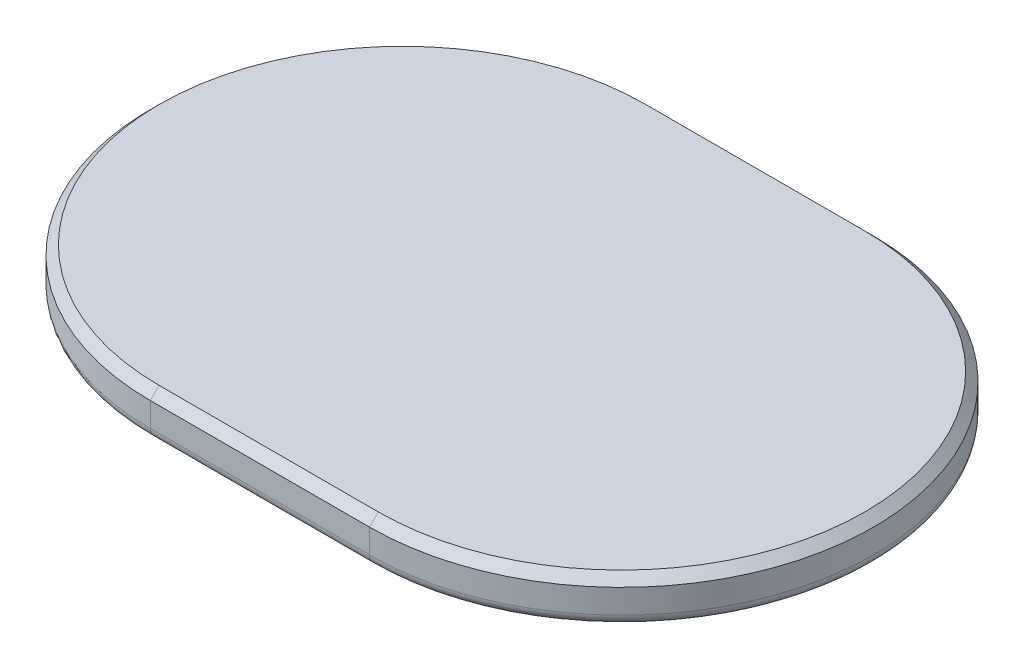
SolidWorks part; units mm, degrees
ref_plane "Front Plane" through (0, 0, 0) normal (0, 0, 1) x (1, 0, 0)
ref_plane "Top Plane" through (0, 0, 0) normal (0, 1, 0) x (1, 0, 0)
ref_plane "Right Plane" through (0, 0, 0) normal (1, 0, 0) x (0, 0, -1)
sketch "Sketch1" plane through (0, 0, 0) normal (0, 1, 0) x (1, 0, 0)
  line L0 (-10, 0) -> (10, 0) construction
  line L1 (-10, 23) -> (10, 23)
  line L2 (-10, -23) -> (10, -23)
  arc A0 (-10, 23) -> (-10, -23) centre (-10, 0) ccw
  arc A1 (10, -23) -> (10, 23) centre (10, 0) ccw
  point P2 (0, 0)
  dimension "D1" = 23
  dimension "D2" = 20
extrude "Boss-Extrude1" add sketch "Sketch1" along normal blind 4
chamfer "Chamfer1" distance 0.8 angle 45 4 edges at (0, 4, -23) (33, 4, 0) (0, 4, 23) (-33, 4, 0)
fillet "Fillet1" radius 1 4 edges at (0, 0, 23) (33, 0, 0) (0, 0, -23) (-33, 0, 0)
